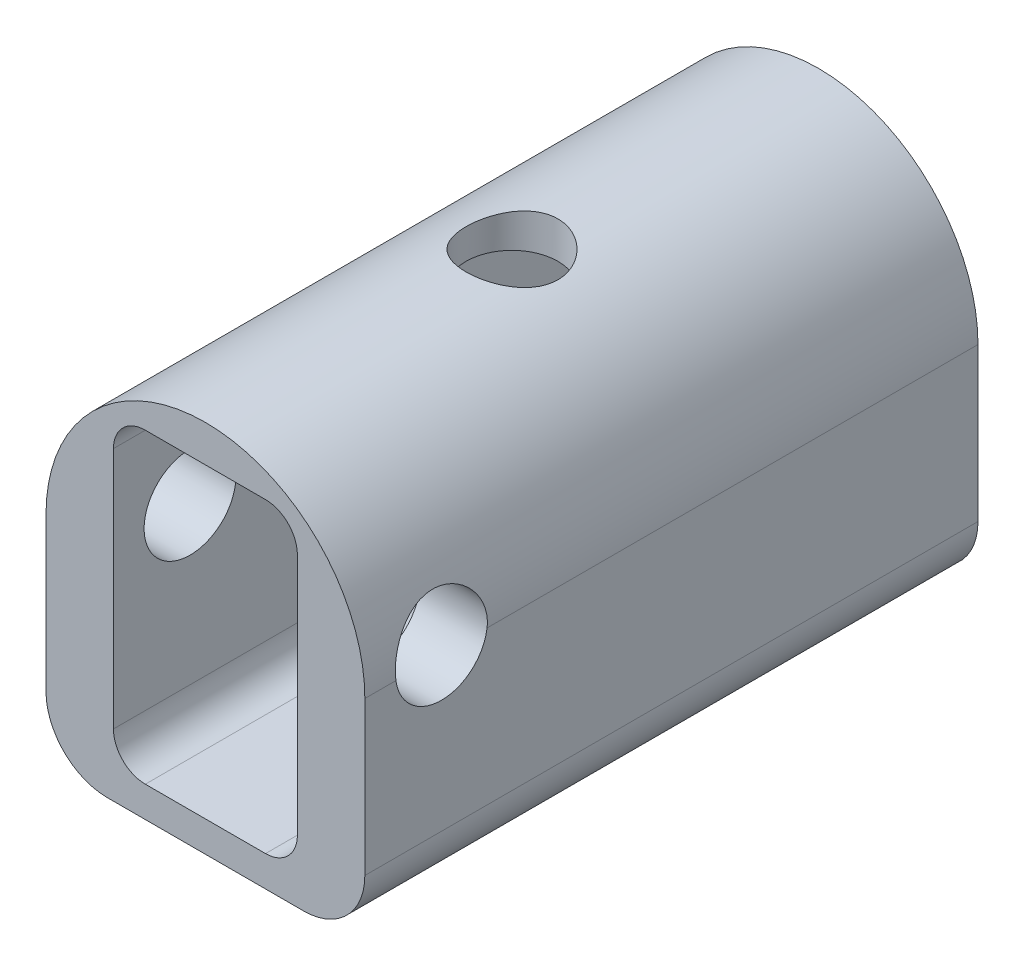
SolidWorks part; units mm, degrees
ref_plane "Front Plane" through (0, 0, 0) normal (0, 0, 1) x (1, 0, 0)
ref_plane "Top Plane" through (0, 0, 0) normal (0, 1, 0) x (1, 0, 0)
ref_plane "Right Plane" through (0, 0, 0) normal (1, 0, 0) x (0, 0, -1)
sketch "Sketch1" plane through (0, 0, 0) normal (0, 0, 1) x (1, 0, 0)
  line L2 (11, 49.8) -> (11, 10.2)
  line L3 (16.2, 5) -> (35.8, 5)
  line L4 (41, 49.8) -> (41, 10.2)
  line L7 (16.2, 55) -> (35.8, 55)
  line L9 (0, 35) -> (0, 0)
  line L12 (0, 0) -> (52, 0)
  line L13 (52, 0) -> (52, 35)
  arc A5 (52, 35) -> (0, 35) centre (26, 35) ccw
  arc A6 (41, 49.8) -> (35.8, 55) centre (35.8, 49.8) ccw
  arc A7 (11, 49.8) -> (16.2, 55) centre (16.2, 49.8) cw
  arc A8 (41, 10.2) -> (35.8, 5) centre (35.8, 10.2) cw
  arc A9 (16.2, 5) -> (11, 10.2) centre (16.2, 10.2) cw
  point P2 (79.801, -33.4895)
  point P3 (0, 0)
  dimension "D4" = 11
  dimension "D6" = 30
  dimension "D5" = 5.2
  dimension "D3" = 5.2
  dimension "D1" = 50
  dimension "D2" = 52
  dimension "D7" = 5
  dimension "D8" = 35
extrude "Boss-Extrude1" add sketch "Sketch1" along normal blind 100
fillet "Fillet3" radius 10 2 edges at (0, 0, 50) (52, 0, 50)
ref_plane "Plane1" through (0, 70, 0) normal (0, 1, 0) x (1, 0, 0)
sketch "Sketch2" plane through (0, 70, 0) normal (0, 1, 0) x (1, 0, 0)
  line L0 (0, -100) -> (52, -100) construction
  line L2 (10, -100) -> (10, 0) construction
  circle A0 centre (26, -50) radius 7.5
  point P6 (0, -3.8949)
  dimension "D1" = 15
  dimension "D2" = 50
  dimension "D3" = 16
extrude "Cut-Extrude1" cut sketch "Sketch2" against normal through all
sketch "Sketch3" plane through (0, 0, 0) normal (1, 0, 0) x (0, 0, -1)
  line L0 (-100, 35) -> (-100, 10) construction
  line L3 (-100, 35) -> (0, 35) construction
  circle A0 centre (-87.5, 36) radius 7.5
  point P2 (-89.5339, 33.1037)
  point P5 (-80, 36.6956)
  point P7 (-88.3649, 35)
  dimension "D3" = 15
  dimension "D1" = 12.5
  dimension "D2" = 1
extrude "Cut-Extrude5" cut sketch "Sketch3" against normal through all and the other way through all
